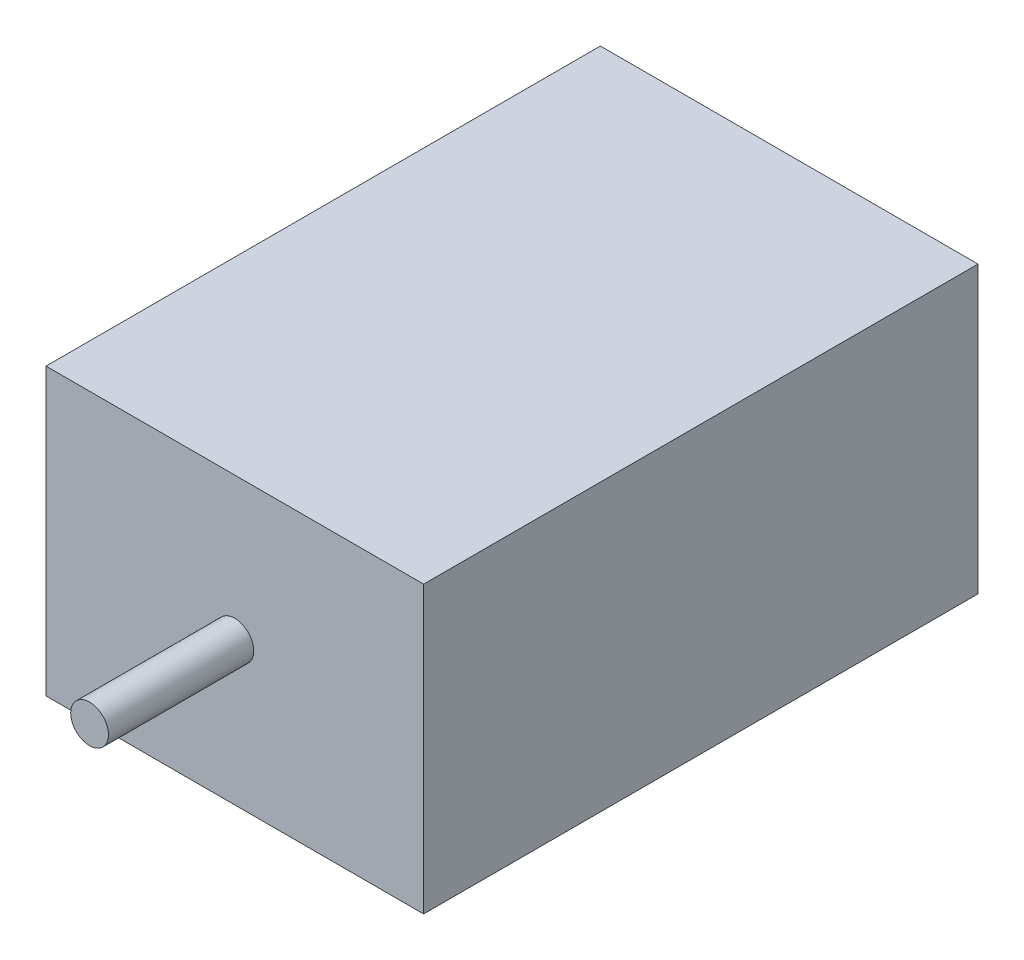
SolidWorks part; units mm, degrees
ref_plane "Front Plane" through (0, 0, 0) normal (0, 0, 1) x (1, 0, 0)
ref_plane "Top Plane" through (0, 0, 0) normal (0, 1, 0) x (1, 0, 0)
ref_plane "Right Plane" through (0, 0, 0) normal (1, 0, 0) x (0, 0, -1)
sketch "Sketch1" plane through (0, 0, 0) normal (0, 0, 1) x (1, 0, 0)
  line L1 (0, 0) -> (19.812, 0)
  line L2 (0, 0) -> (0, 14.986)
  line L3 (0, 14.986) -> (19.812, 14.986)
  line L4 (19.812, 0) -> (19.812, 14.986)
  dimension "D1" = 14.986
  dimension "D2" = 19.812
extrude "Boss-Extrude1" add sketch "Sketch1" along normal blind 29.083
sketch "Sketch2" plane through (0, 0, 29.083) normal (0, 0, 1) x (1, 0, 0)
  line L1 (9.906, 7.493) -> (19.812, 7.493)
  line L2 (9.906, 7.493) -> (9.906, 14.986)
  line L3 (9.906, 14.986) -> (19.812, 14.986)
  line L4 (19.812, 7.493) -> (19.812, 14.986)
  line L5 (0, 0) -> (9.906, 0)
  line L6 (0, 0) -> (0, 7.493)
  line L7 (0, 7.493) -> (9.906, 7.493)
  line L8 (9.906, 0) -> (9.906, 7.493)
  circle A0 centre (9.906, 7.493) radius 0.9906
  dimension "D1" = 1.9812
extrude "Boss-Extrude2" add sketch "Sketch2" along normal blind 7.62 contours A0
